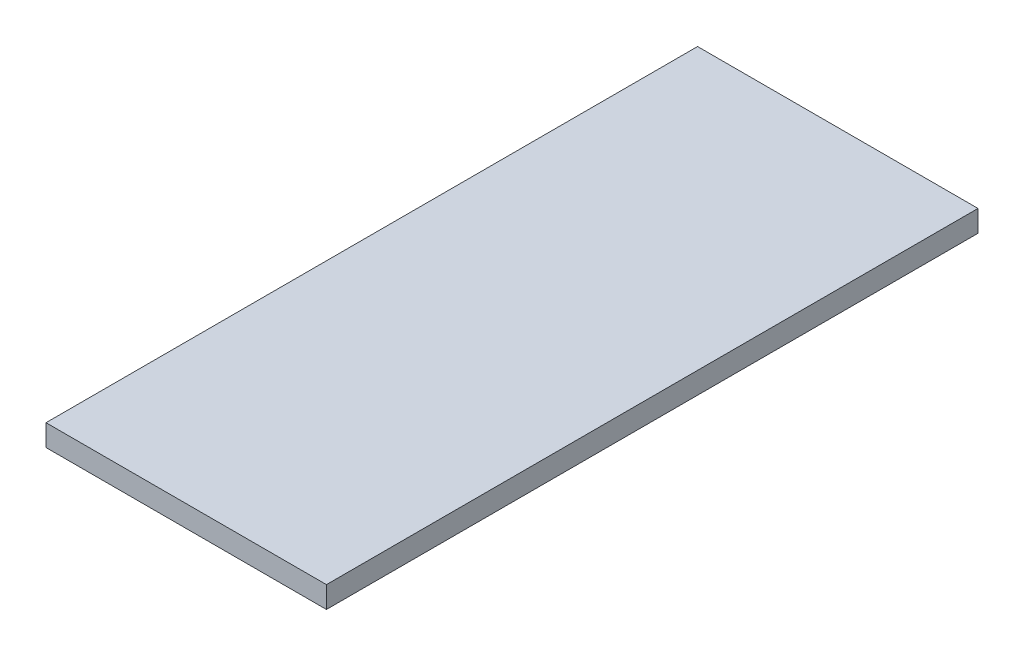
SolidWorks part; units mm, degrees
ref_plane "Plano frontal" through (0, 0, 0) normal (0, 0, 1) x (1, 0, 0)
ref_plane "Plano superior" through (0, 0, 0) normal (0, 1, 0) x (1, 0, 0)
ref_plane "Plano direito" through (0, 0, 0) normal (1, 0, 0) x (0, 0, -1)
sketch "Sketch1" plane through (0, 0, 0) normal (0, 1, 0) x (1, 0, 0)
  line L1 (0, 0) -> (260.4, 0)
  line L2 (0, 0) -> (0, 605)
  line L3 (0, 605) -> (260.4, 605)
  line L4 (260.4, 0) -> (260.4, 605)
  line L5 (130.2, 605) -> (130.2, 0) construction
  line L6 (0, 302.5) -> (260.4, 302.5) construction
  point P172 (130.2, 302.5)
  dimension "D1" = 260.4
  dimension "D2" = 605
extrude "Boss-Extrude1" add sketch "Sketch1" along normal blind 20
